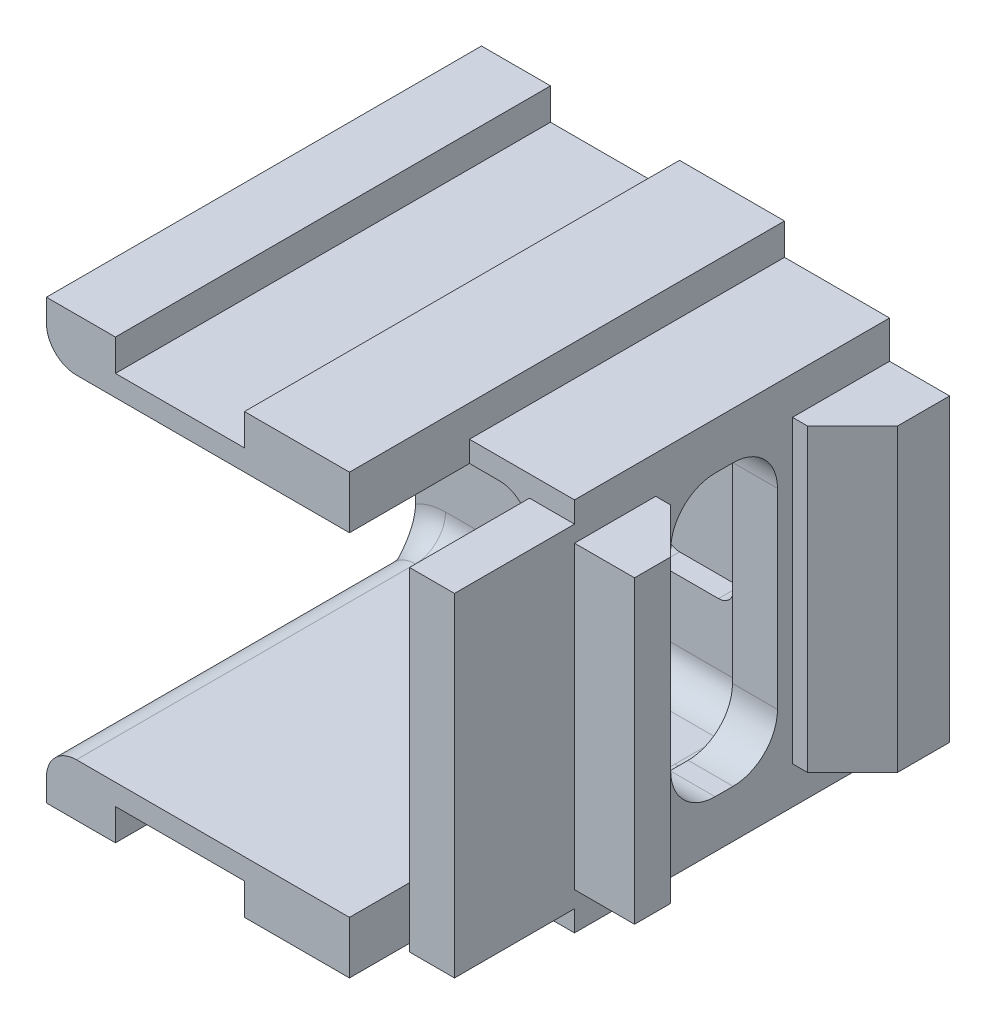
SolidWorks part; units mm, degrees
ref_plane "Front Plane" through (0, 0, 0) normal (1, 0, 0) x (0, 1, 0)
ref_plane "Top Plane" through (0, 0, 0) normal (0, 0, 1) x (0, 1, 0)
ref_plane "Right Plane" through (0, 0, 0) normal (0, 1, 0) x (-1, 0, 0)
sketch "Sketch2" plane through (0, 0, 0) normal (1, 0, 0) x (0, 1, 0)
  line L1 (5, 5.25) -> (-5, 5.25)
  line L2 (5, 5.25) -> (5, -5.25)
  line L3 (5, -5.25) -> (-5, -5.25)
  line L4 (-5, 5.25) -> (-5, -5.25)
  line L5 (5, 5.25) -> (-5, -5.25) construction
  line L6 (5, -5.25) -> (-5, 5.25) construction
  point P0 (0, 0)
  dimension "D1" = 10.5
  dimension "D2" = 10
extrude "Boss-Extrude1" add sketch "Sketch2" along normal blind 2
sketch "Sketch3" plane through (0, 0, 0) normal (-1, 0, 0) x (0, -1, 0)
  line L1 (-6.25, -5.25) -> (6.25, -5.25)
  line L2 (-6.25, -5.25) -> (-6.25, 9.25)
  line L3 (-6.25, 9.25) -> (6.25, 9.25)
  line L4 (5, -5.25) -> (5, 5.25)
  line L5 (5, 5.25) -> (-5, 5.25)
  line L6 (-5, 5.25) -> (-5, -5.25)
  line L7 (-5, -5.25) -> (5, -5.25)
  line L8 (5, -5.25) -> (5, 5.25) construction
  line L9 (5, 5.25) -> (-5, 5.25) construction
  line L10 (-5, 5.25) -> (-5, -5.25) construction
  line L11 (-5, -5.25) -> (5, -5.25) construction
  line L12 (6.25, -5.25) -> (6.25, 9.25)
  point P8 (0, -5.25)
  point P9 (0, -5.25)
  dimension "D2" = 12.5
  dimension "D3" = 14.5
  dimension "D1" = 0
extrude "Boss-Extrude2" add sketch "Sketch3" along normal blind 3.5
sketch "Sketch4" plane through (-3.5, 0, 0) normal (-1, 0, 0) x (0, -1, 0)
  line L1 (-7.3, -5.25) -> (7.3, -5.25)
  line L2 (-7.3, -5.25) -> (-7.3, 9.25)
  line L3 (-7.3, 9.25) -> (7.3, 9.25)
  line L4 (-6.25, 9.25) -> (-6.25, -5.25)
  line L5 (-6.25, -5.25) -> (6.25, -5.25)
  line L6 (6.25, -5.25) -> (6.25, 9.25)
  line L7 (6.25, 9.25) -> (-6.25, 9.25)
  line L8 (-6.25, 9.25) -> (-6.25, -5.25) construction
  line L9 (-6.25, -5.25) -> (6.25, -5.25) construction
  line L10 (6.25, -5.25) -> (6.25, 9.25) construction
  line L11 (6.25, 9.25) -> (-6.25, 9.25) construction
  line L12 (7.3, -5.25) -> (7.3, 9.25)
  point P9 (0, -5.25)
  point P10 (0, -5.25)
  dimension "D2" = 14.6
  dimension "D1" = 0
extrude "Boss-Extrude3" add sketch "Sketch4" along normal blind 3.5
sketch "Sketch5" plane through (-7, 0, 0) normal (-1, 0, 0) x (0, -1, 0)
  line L1 (-6.25, -5.25) -> (6.25, -5.25)
  line L2 (-6.25, -5.25) -> (-6.25, 9.25)
  line L3 (-6.25, 9.25) -> (6.25, 9.25)
  line L4 (-7.3, 9.25) -> (-7.3, -5.25)
  line L5 (-7.3, -5.25) -> (7.3, -5.25)
  line L6 (7.3, -5.25) -> (7.3, 9.25)
  line L7 (7.3, 9.25) -> (-7.3, 9.25)
  line L8 (-7.3, 9.25) -> (-7.3, -5.25) construction
  line L9 (-7.3, -5.25) -> (7.3, -5.25) construction
  line L10 (7.3, -5.25) -> (7.3, 9.25) construction
  line L11 (7.3, 9.25) -> (-7.3, 9.25) construction
  line L12 (6.25, -5.25) -> (6.25, 9.25)
  point P8 (0, -5.25)
  point P9 (0, -5.25)
  dimension "D2" = 12.5
  dimension "D1" = 0
extrude "Boss-Extrude4" add sketch "Sketch5" along normal blind 4.3
sketch "Sketch6" plane through (-11.3, 0, 0) normal (-1, 0, 0) x (0, -1, 0)
  line L0 (6.25, 9.25) -> (6.25, -5.25) construction
  line L1 (6.25, -5.25) -> (7.3, -5.25) construction
  line L2 (7.3, -5.25) -> (7.3, 9.25) construction
  line L3 (7.3, 9.25) -> (6.25, 9.25) construction
  line L4 (-6.25, 9.25) -> (-6.25, -5.25) construction
  line L5 (-6.25, -5.25) -> (6.25, -5.25) construction
  line L6 (6.25, -5.25) -> (6.25, 9.25) construction
  line L7 (6.25, 9.25) -> (-6.25, 9.25) construction
  line L8 (-6.25, -5.25) -> (-6.25, 9.25) construction
  line L9 (-6.25, 9.25) -> (-7.3, 9.25) construction
  line L10 (-7.3, 9.25) -> (-7.3, -5.25) construction
  line L11 (-7.3, -5.25) -> (-6.25, -5.25) construction
  line L12 (6.25, 9.25) -> (6.25, -5.25) construction
  line L13 (6.25, -5.25) -> (7.3, -5.25)
  line L14 (7.3, -5.25) -> (7.3, 9.25)
  line L15 (7.3, 9.25) -> (6.25, 9.25)
  line L16 (-6.25, 9.25) -> (-6.25, -5.25) construction
  line L17 (-6.25, -5.25) -> (6.25, -5.25)
  line L18 (6.25, -5.25) -> (6.25, 9.25) construction
  line L19 (6.25, 9.25) -> (-6.25, 9.25)
  line L20 (-6.25, -5.25) -> (-6.25, 9.25) construction
  line L21 (-6.25, 9.25) -> (-7.3, 9.25)
  line L22 (-7.3, 9.25) -> (-7.3, -5.25)
  line L23 (-7.3, -5.25) -> (-6.25, -5.25)
extrude "Boss-Extrude5" add sketch "Sketch6" along normal blind 2.3
sketch "Sketch8" plane through (0, 0, 9.25) normal (0, 0, 1) x (1, 0, 0)
  line L1 (-13.6, 5.55) -> (-1.5, 5.55)
  line L2 (-13.6, 5.55) -> (-13.6, -5.55)
  line L3 (-13.6, -5.55) -> (-1.5, -5.55)
  line L4 (-1.5, 5.55) -> (-1.5, -5.55)
  line L16 (0, -6.25) -> (0, 6.25)
  line L17 (0, 6.25) -> (-3.5, 6.25)
  line L18 (-3.5, 6.25) -> (-3.5, 7.3)
  line L19 (-3.5, 7.3) -> (-7, 7.3)
  line L20 (-7, 7.3) -> (-7, 6.25)
  line L21 (-7, 6.25) -> (-11.3, 6.25)
  line L22 (-11.3, 6.25) -> (-11.3, 7.3)
  line L23 (-11.3, 7.3) -> (-13.6, 7.3)
  line L24 (-13.6, 7.3) -> (-13.6, -7.3)
  line L25 (-13.6, -7.3) -> (-11.3, -7.3)
  line L26 (-11.3, -7.3) -> (-11.3, -6.25)
  line L27 (-11.3, -6.25) -> (-7, -6.25)
  line L28 (-7, -6.25) -> (-7, -7.3)
  line L29 (-7, -7.3) -> (-3.5, -7.3)
  line L30 (-3.5, -7.3) -> (-3.5, -6.25)
  line L31 (-3.5, -6.25) -> (0, -6.25)
  line L32 (0, -6.25) -> (0, 6.25) construction
  line L33 (0, 6.25) -> (-3.5, 6.25) construction
  line L34 (-3.5, 6.25) -> (-3.5, 7.3) construction
  line L35 (-3.5, 7.3) -> (-7, 7.3) construction
  line L36 (-7, 7.3) -> (-7, 6.25) construction
  line L37 (-7, 6.25) -> (-11.3, 6.25) construction
  line L38 (-11.3, 6.25) -> (-11.3, 7.3) construction
  line L39 (-11.3, 7.3) -> (-13.6, 7.3) construction
  line L40 (-13.6, 7.3) -> (-13.6, -7.3) construction
  line L41 (-13.6, -7.3) -> (-11.3, -7.3) construction
  line L42 (-11.3, -7.3) -> (-11.3, -6.25) construction
  line L43 (-11.3, -6.25) -> (-7, -6.25) construction
  line L44 (-7, -6.25) -> (-7, -7.3) construction
  line L45 (-7, -7.3) -> (-3.5, -7.3) construction
  line L46 (-3.5, -7.3) -> (-3.5, -6.25) construction
  line L47 (-3.5, -6.25) -> (0, -6.25) construction
  point P10 (-13.6, 0)
  point P12 (-13.6, 0)
  dimension "D2" = 0.7
  dimension "D3" = 1.5
  dimension "D1" = 0
extrude "Cut-Extrude1" cut sketch "Sketch8" against normal blind 13
sketch "Sketch10" plane through (0, 0, 9.25) normal (0, 0, 1) x (1, 0, 0)
  line L0 (-1.5, 5.55) -> (-13.6, 5.55) construction
  line L9 (0, 6.25) -> (-3.5, 6.25)
  line L10 (0, 6.25) -> (0, 5.55)
  line L11 (0, 5.55) -> (-3.5, 5.55)
  line L12 (-3.5, 6.25) -> (-3.5, 5.55)
  line L13 (-13.6, -5.55) -> (-1.5, -5.55) construction
  line L14 (0, -6.25) -> (-3.5, -6.25)
  line L15 (0, -6.25) -> (0, -5.55)
  line L16 (0, -5.55) -> (-3.5, -5.55)
  line L17 (-3.5, -6.25) -> (-3.5, -5.55)
extrude "Cut-Extrude6" cut sketch "Sketch10" against normal up to surface (4 mm away) up to face at (1, 0, 5.25)
fillet "Fillet1" radius 1 2 edges at (-13.6, -5.55, 2.75) (-13.6, 5.55, 2.75)
sketch "Sketch13" plane through (0, 0, 0) normal (1, 0, 0) x (0, 0, -1)
  line L0 (-1.845, 0.01) -> (-1.845, -3.18) construction
  line L1 (-0.565, -4.46) -> (0.035, -4.46) construction
  line L2 (1.315, -3.18) -> (1.315, 0.01) construction
  line L3 (1.315, 3.2) -> (1.315, 0.01) construction
  line L4 (-0.565, 4.48) -> (0.035, 4.48) construction
  line L5 (-1.845, 0.01) -> (-1.845, 3.2) construction
  line L6 (-1.845, 0.01) -> (-1.845, -3.18) construction
  line L7 (-0.565, -4.46) -> (0.035, -4.46) construction
  line L8 (1.315, -3.18) -> (1.315, 0.01) construction
  line L9 (1.315, 3.2) -> (1.315, 0.01) construction
  line L10 (-0.565, 4.48) -> (0.035, 4.48) construction
  line L11 (-1.845, 0.01) -> (-1.845, 3.2) construction
  line L12 (-2.045, 0.01) -> (-2.045, -3.18)
  line L13 (-0.565, -4.66) -> (0.035, -4.66)
  line L14 (1.515, -3.18) -> (1.515, 0.01)
  line L15 (1.515, 3.2) -> (1.515, 0.01)
  line L16 (-0.565, 4.68) -> (0.035, 4.68)
  line L17 (-2.045, 0.01) -> (-2.045, 3.2)
  arc A0 (-1.845, -3.18) -> (-0.565, -4.46) centre (-0.565, -3.18) ccw construction
  arc A1 (0.035, -4.46) -> (1.315, -3.18) centre (0.035, -3.18) ccw construction
  arc A2 (1.315, 3.2) -> (0.035, 4.48) centre (0.035, 3.2) ccw construction
  arc A3 (-0.565, 4.48) -> (-1.845, 3.2) centre (-0.565, 3.2) ccw construction
  arc A4 (-1.845, -3.18) -> (-0.565, -4.46) centre (-0.565, -3.18) ccw construction
  arc A5 (0.035, -4.46) -> (1.315, -3.18) centre (0.035, -3.18) ccw construction
  arc A6 (1.315, 3.2) -> (0.035, 4.48) centre (0.035, 3.2) ccw construction
  arc A7 (-0.565, 4.48) -> (-1.845, 3.2) centre (-0.565, 3.2) ccw construction
  arc A8 (-2.045, -3.18) -> (-0.565, -4.66) centre (-0.565, -3.18) ccw
  arc A9 (0.035, -4.66) -> (1.515, -3.18) centre (0.035, -3.18) ccw
  arc A10 (1.515, 3.2) -> (0.035, 4.68) centre (0.035, 3.2) ccw
  arc A11 (-0.565, 4.68) -> (-2.045, 3.2) centre (-0.565, 3.2) ccw
  dimension "D1" = 0.2
extrude "Cut-Extrude9" cut sketch "Sketch13" against normal through all both and the other way through all
sketch "Sketch15" plane through (0, 0, -3.75) normal (0, 0, 1) x (1, 0, 0)
  line L1 (-3, 2.5) -> (-6, 2.5)
  line L2 (-3, 2.5) -> (-3, -2.5)
  line L3 (-3, -2.5) -> (-6, -2.5)
  line L4 (-13.6, 6.55) -> (-13.6, -6.55)
  line L5 (-12.6, -5.55) -> (-1.5, -5.55)
  line L6 (-1.5, -5.55) -> (-1.5, 5.55)
  line L7 (-1.5, 5.55) -> (-12.6, 5.55)
  line L8 (-13.6, 6.55) -> (-13.6, -6.55)
  line L9 (-12.6, -5.55) -> (-1.5, -5.55)
  line L10 (-1.5, -5.55) -> (-1.5, 5.55)
  line L11 (-1.5, 5.55) -> (-12.6, 5.55)
  line L12 (-6, 2.5) -> (-6, -2.5)
  arc A2 (-12.6, -5.55) -> (-13.6, -6.55) centre (-12.6, -6.55) ccw
  arc A3 (-13.6, 6.55) -> (-12.6, 5.55) centre (-12.6, 6.55) ccw
  arc A4 (-12.6, -5.55) -> (-13.6, -6.55) centre (-12.6, -6.55) ccw
  arc A5 (-13.6, 6.55) -> (-12.6, 5.55) centre (-12.6, 6.55) ccw
  point P12 (-1.5, 0)
  point P13 (-3, 0)
  point P14 (0, 0)
  dimension "D2" = 1.5
  dimension "D3" = 3
  dimension "D4" = 5
  dimension "D1" = 0
extrude "Boss-Extrude6" add sketch "Sketch15" along normal blind 0.7
fillet "Fillet5" radius 0.5 4 edges at (-6, 2.5, -3.4) (-6, -2.5, -3.4) (-3, 2.5, -3.4) (-3, -2.5, -3.4)
fillet "Fillet3" radius 1 2 edges at (-1.5, 5.55, 1.1) (-1.5, -5.55, 1.1)
fillet "Fillet4" radius 1 7 edges at (-13.3071, -5.8429, -3.05) (-13.3071, 5.8429, -3.05) (-7.55, 5.55, -3.05) (-1.7929, 5.2571, -3.05) (-1.5, 0, -3.05) (-1.7929, -5.2571, -3.05) (-7.55, -5.55, -3.05)
sketch "Sketch14" plane through (2, 0, 0) normal (1, 0, 0) x (0, 0, -1)
  line L0 (-5.25, -5) -> (5.25, -5) construction
  line L1 (-2.545, -5) -> (2.015, -5)
  line L2 (-2.545, -5) -> (-2.545, 5)
  line L3 (-2.545, 5) -> (2.015, 5)
  line L4 (2.015, -5) -> (2.015, 5)
  line L5 (5.25, 5) -> (-5.25, 5) construction
  line L6 (-2.045, 3.2) -> (-2.045, -3.18) construction
  line L7 (1.515, -3.18) -> (1.515, 3.2) construction
  dimension "D1" = 0.5
  dimension "D2" = 0.5
extrude "Cut-Extrude10" cut sketch "Sketch14" against normal up to surface (2 mm away) and the other way through all up to face at (0, 0, 2.4167)
chamfer "Chamfer4" distance 1.5 angle 45 2 edges at (2, 0, -2.015) (2, 0, 2.545)
